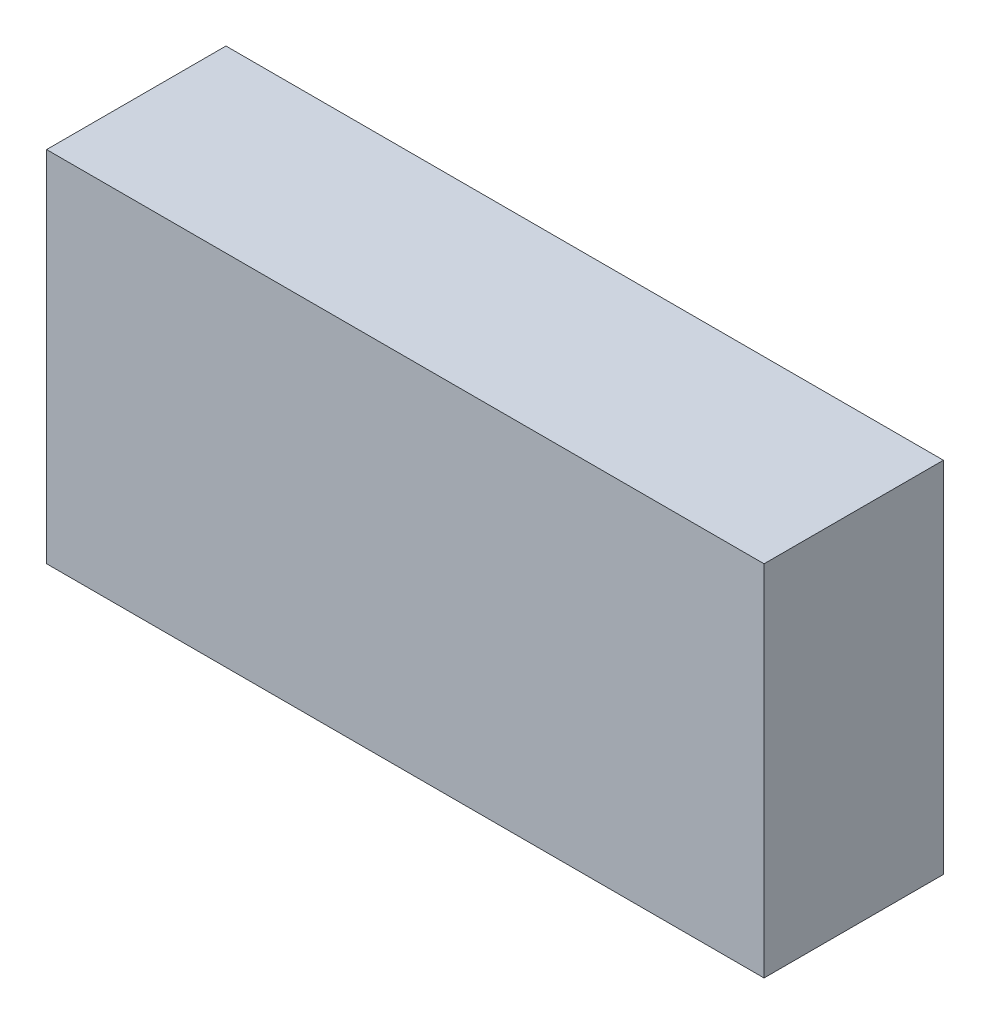
SolidWorks part; units mm, degrees
ref_plane "Front Plane" through (0, 0, 0) normal (0, 0, 1) x (1, 0, 0)
ref_plane "Top Plane" through (0, 0, 0) normal (0, 1, 0) x (1, 0, 0)
ref_plane "Right Plane" through (0, 0, 0) normal (1, 0, 0) x (0, 0, -1)
sketch "Sketch1" plane through (0, 0, 0) normal (0, 0, 1) x (1, 0, 0)
  line L0 (-0.8, 0.4) -> (0.8, 0.4)
  line L1 (0.8, 0.4) -> (0.8, -0.4)
  line L2 (0.8, -0.4) -> (-0.8, -0.4)
  line L3 (-0.8, -0.4) -> (-0.8, 0.4)
extrude "Component_Outline" add sketch "Sketch1" along normal blind 0.4 separate body
sketch3d "3DSketch1"
  line L0 (0, 0, 0) -> (1, 0, 0)
  line L1 (0, 0, 0) -> (0, 1, 0)
  line L2 (0, 0, 0) -> (0, 0, 1)
  point P0 (0, 0, 0)
